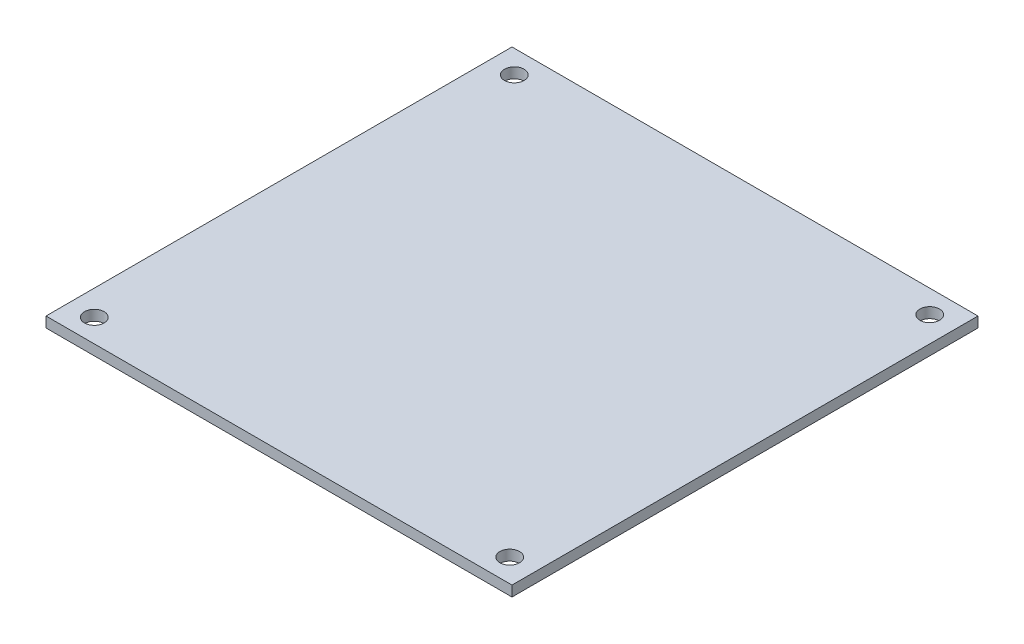
SolidWorks part; units mm, degrees
ref_plane "Front Plane" through (0, 0, 0) normal (0, 0, 1) x (1, 0, 0)
ref_plane "Top Plane" through (0, 0, 0) normal (0, 1, 0) x (1, 0, 0)
ref_plane "Right Plane" through (0, 0, 0) normal (1, 0, 0) x (0, 0, -1)
sketch "Sketch1" plane through (0, 0, 0) normal (0, 1, 0) x (1, 0, 0)
  line L0 (0, 35.56) -> (0, -35.56) construction
  line L1 (-35.56, 35.56) -> (35.56, 35.56)
  line L2 (-35.56, 35.56) -> (-35.56, -35.56)
  line L3 (-35.56, -35.56) -> (35.56, -35.56)
  line L4 (35.56, 35.56) -> (35.56, -35.56)
  line L7 (-35.56, 0) -> (35.56, 0) construction
  circle A0 centre (-31.7, 32.05) radius 1.5
  circle A1 centre (31.7, 32.05) radius 1.5
  circle A2 centre (31.7, -32.05) radius 1.5
  circle A3 centre (-31.7, -32.05) radius 1.5
  point P0 (0, 0)
  dimension "D4" = 3
  dimension "D1" = 71.12
  dimension "D2" = 71.12
  dimension "D3" = 63.4
  dimension "D5" = 64.1
extrude "Boss-Extrude1" add sketch "Sketch1" along normal blind 1.5875
